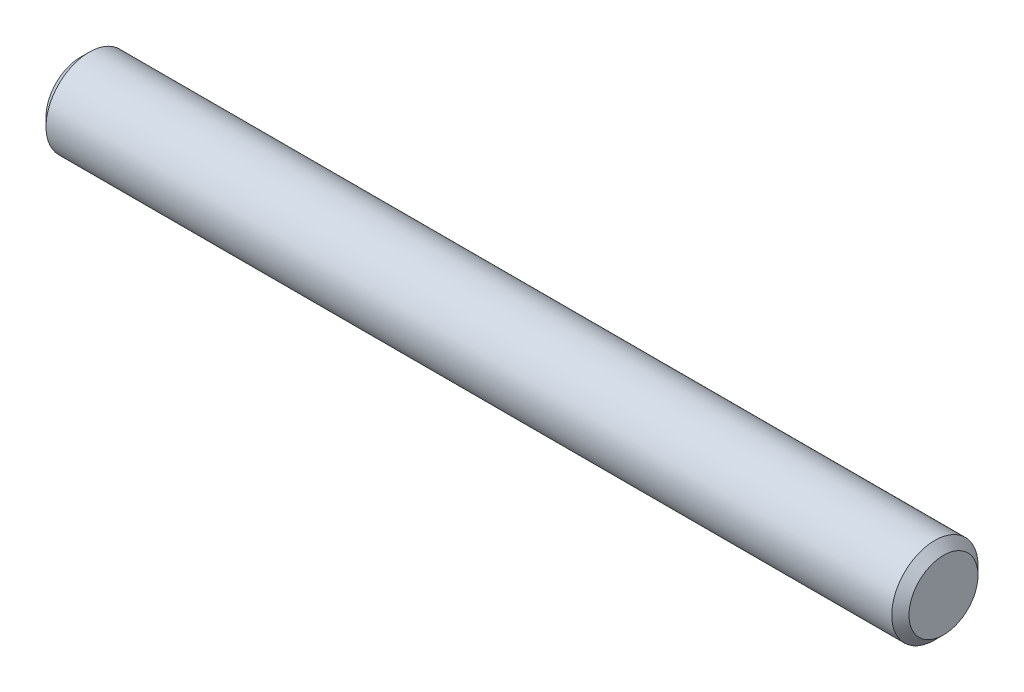
SolidWorks part; units mm, degrees
ref_plane "Front" through (0, 0, 0) normal (0, 0, 1) x (1, 0, 0)
ref_plane "Top" through (0, 0, 0) normal (0, 1, 0) x (1, 0, 0)
ref_plane "Right" through (0, 0, 0) normal (1, 0, 0) x (0, 0, -1)
sketch "Sketch1" plane through (0, 0, 0) normal (0, 0, 1) x (1, 0, 0)
  line L0 (-31.75, 0) -> (31.75, 0) construction
  line L1 (31.75, 3.175) -> (31.75, -3.175) construction
  line L2 (-31.75, 3.175) -> (-31.75, -3.175) construction
  dimension "Length" = 63.5
  dimension "Diameter" = 6.35
sketch "Sketch2" plane through (0, 0, 0) normal (1, 0, 0) x (0, 0, -1)
  circle A0 centre (0, 0) radius 3.175
extrude "Extrude1" add sketch "Sketch2" against normal up to vertex (31.75 mm away) and the other way up to vertex (31.75 mm away) up to point (-31.75, 3.175, 0) other way up to point (31.75, 3.175, 0)
chamfer "Chamfer1" distance 0.635 angle 45 2 edges at (31.75, 0, -3.175) (-31.75, 0, -3.175)
equation "\"D1@Chamfer1\" = \"Diameter@Sketch1\"*.1"
